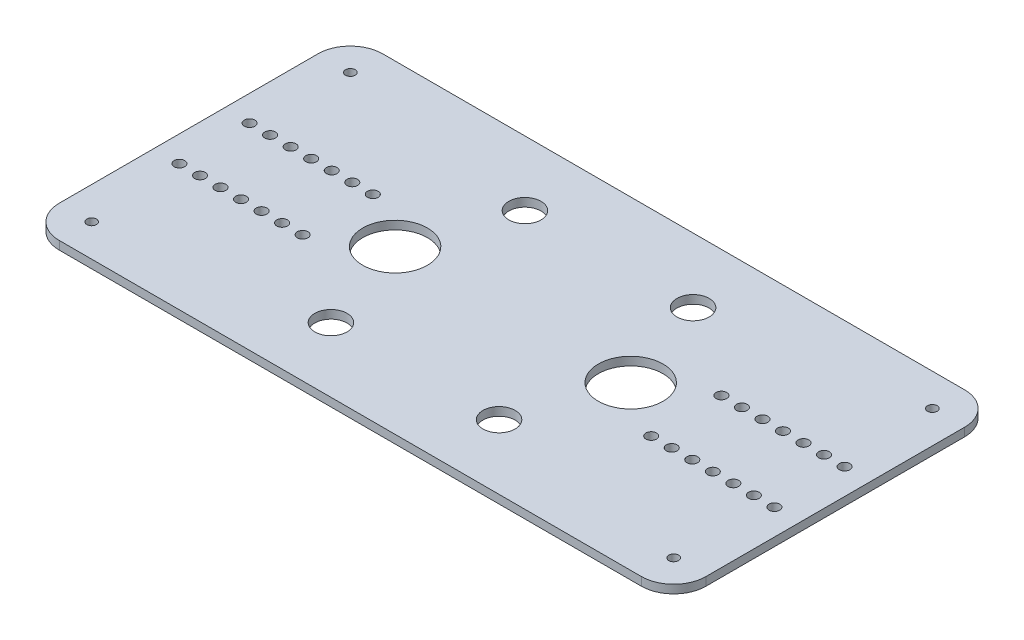
SolidWorks part; units mm, degrees
ref_plane "Front Plane" through (0, 0, 0) normal (0, 0, 1) x (1, 0, 0)
ref_plane "Top Plane" through (0, 0, 0) normal (0, 1, 0) x (1, 0, 0)
ref_plane "Right Plane" through (0, 0, 0) normal (1, 0, 0) x (0, 0, -1)
sketch "Sketch1" plane through (0, 0, 0) normal (0, 1, 0) x (1, 0, 0)
  line L1 (0, 0) -> (200, 0)
  line L2 (0, 0) -> (0, -100)
  line L3 (0, -100) -> (200, -100)
  line L4 (200, 0) -> (200, -100)
  dimension "D1" = 100
  dimension "D2" = 200
extrude "Boss-Extrude1" add sketch "Sketch1" along normal blind 2.6 contours L1 L4 L3 L2
fillet "Fillet1" radius 10 4 edges at (0, 1.3, 0) (0, 1.3, 100) (200, 1.3, 100) (200, 1.3, 0)
sketch "Sketch6" plane through (0, 0, 0) normal (0, -1, 0) x (1, 0, 0)
  line L0 (200, 10) -> (200, 90) construction
  line L1 (10, 0) -> (190, 0) construction
  circle A0 centre (190, 10) radius 1.5
  dimension "D1" = 3
  dimension "D2" = 10
  dimension "D3" = 10
sketch "Sketch8" plane through (0, 0, 0) normal (0, -1, 0) x (1, 0, 0)
  line L0 (200, 10) -> (200, 90) construction
  line L2 (200, 50) -> (0, 50) construction
  line L3 (0, 10) -> (0, 90) construction
  line L4 (200, 10) -> (200, 90) construction
  circle A0 centre (192, 60.85) radius 1.65
  circle A1 centre (192, 39.15) radius 1.65
  dimension "D1" = 3.3
  dimension "D2" = 10.85
  dimension "D3" = 8
  dimension "D4" = 8
  dimension "D5" = 10.85
  dimension "D6" = 3.3
extrude "Cut-Extrude4" cut sketch "Sketch8" against normal blind 2.6
pattern_linear "LPattern1" count 7 spacing 6.35 along (-1, 0, 0) of "Cut-Extrude4"
ref_plane "Plane1" through (100, 0, 0) normal (1, 0, 0) x (0, 0, -1)
mirror "Mirror1" about plane through (100, 0, 0) normal (1, 0, 0) of "Cut-Extrude4", "LPattern1"
extrude "Cut-Extrude6" cut sketch "Sketch6" against normal blind 2.6 contours A0
ref_plane "Plane14" through (0, 0, 50) normal (0, 0, 1) x (1, 0, 0)
mirror "Mirror5" about plane through (100, 0, 0) normal (1, 0, 0) of "Cut-Extrude6"
mirror "Mirror6" about plane through (0, 0, 50) normal (0, 0, 1) of "Mirror5", "Cut-Extrude6"
sketch "Sketch13" plane through (0, 2.6, 0) normal (0, 1, 0) x (1, 0, 0)
  line L0 (100, -44) -> (100, 44) construction
  line L1 (-1.43, -50) -> (1.43, -50) construction
  circle A0 centre (74, -80) radius 4.9806
  dimension "D1" = 26
  dimension "D2" = 30
extrude "Cut-Extrude7" cut sketch "Sketch13" against normal blind 2.6
mirror "Mirror7" about plane through (0, 0, 50) normal (0, 0, 1) of "Cut-Extrude7"
mirror "Mirror8" about plane through (100, 0, 0) normal (1, 0, 0) of "Cut-Extrude7", "Mirror7"
sketch "Sketch15" plane through (0, 0, 0) normal (0, -1, 0) x (1, 0, 0)
  circle A0 centre (63.5719, 49.722) radius 10
  dimension "D1" = 20
extrude "Cut-Extrude8" cut sketch "Sketch15" against normal blind 2.6
mirror "Mirror9" about plane through (100, 0, 0) normal (1, 0, 0) of "Cut-Extrude8"
